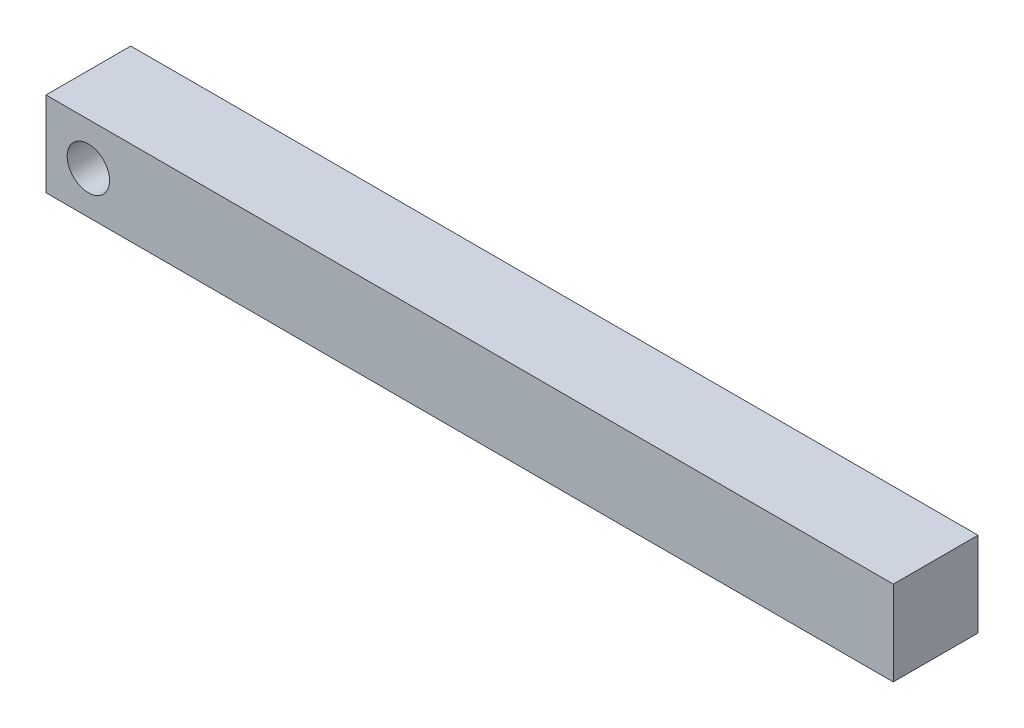
SolidWorks part; units mm, degrees
ref_plane "Front Plane" through (0, 0, 0) normal (0, 0, 1) x (1, 0, 0)
ref_plane "Top Plane" through (0, 0, 0) normal (0, 1, 0) x (1, 0, 0)
ref_plane "Right Plane" through (0, 0, 0) normal (1, 0, 0) x (0, 0, -1)
sketch "Sketch1" plane through (0, 0, 0) normal (0, 0, 1) x (1, 0, 0)
  line L1 (-100, 10) -> (100, 10)
  line L2 (-100, 10) -> (-100, -10)
  line L3 (-100, -10) -> (100, -10)
  line L4 (100, 10) -> (100, -10)
  line L5 (-100, 10) -> (100, -10) construction
  line L6 (-100, -10) -> (100, 10) construction
  point P0 (0, 0)
  dimension "D1" = 200
  dimension "D2" = 20
extrude "Boss-Extrude2" add sketch "Sketch1" along normal blind 20
sketch "Sketch3" plane through (0, 0, 20) normal (0, 0, 1) x (1, 0, 0)
  line L0 (-100, 10) -> (-100, -10) construction
  line L1 (-100, -10) -> (100, -10) construction
  circle A0 centre (-90, 0) radius 5
  dimension "D1" = 10
  dimension "D2" = 10
  dimension "D3" = 10
extrude "Cut-Extrude1" cut sketch "Sketch3" against normal through all
equation "\"segment width\" = 60"
equation "\"segment support width\"= 20"
equation "\"servo hole\"= 10'arbitrary atm"
equation "\"segment length 1\"= 200"
equation "\"segment length 2\"= 200"
equation "\"segment length 3\"= 200"
equation "\"segment length 4\"= 100"
equation "\"segment length 5\"= 100"
equation "\"base diameter\"= 100"
equation "\"base height\"= 50"
equation "\"D1@Sketch1\"= \"segment length 3\""
equation "\"D2@Sketch1\"=\"segment support width\""
equation "\"D1@Boss-Extrude2\"=\"segment support width\""
equation "\"D1@Sketch3\"=\"servo hole\""
equation "\"D2@Sketch3\"=\"segment support width\"/2"
equation "\"D3@Sketch3\"=\"segment support width\"/2"
